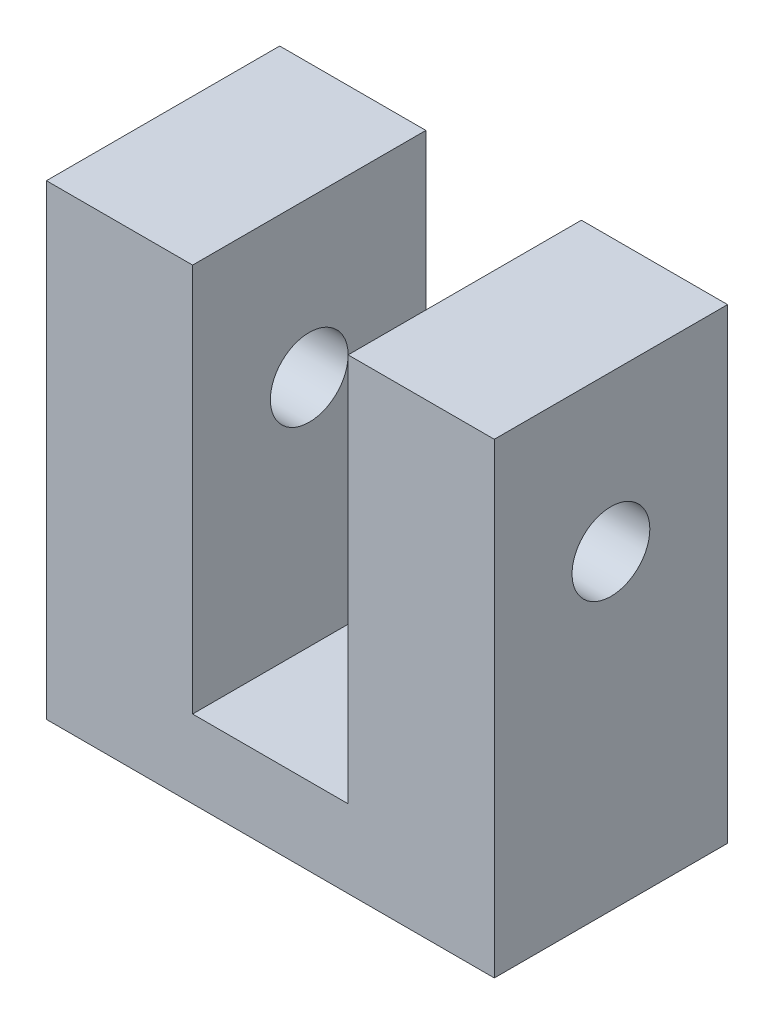
SolidWorks part; units mm, degrees
ref_plane "Front Plane" through (0, 0, 0) normal (0, 0, 1) x (1, 0, 0)
ref_plane "Top Plane" through (0, 0, 0) normal (0, 1, 0) x (1, 0, 0)
ref_plane "Right Plane" through (0, 0, 0) normal (1, 0, 0) x (0, 0, -1)
sketch "Sketch1" plane through (0, 0, 0) normal (0, 0, 1) x (1, 0, 0)
  line L0 (-18.288, 0) -> (-18.288, 38.1)
  line L1 (-18.288, 38.1) -> (-6.35, 38.1)
  line L2 (-6.35, 38.1) -> (-6.35, 6.35)
  line L3 (0, -55) -> (0, 55) construction
  line L4 (6.35, 38.1) -> (6.35, 6.35)
  line L5 (18.288, 38.1) -> (6.35, 38.1)
  line L6 (18.288, 0) -> (18.288, 38.1)
  line L7 (-6.35, 6.35) -> (6.35, 6.35)
  line L8 (-18.288, 0) -> (18.288, 0)
  dimension "D1" = 12.7
  dimension "D2" = 36.576
  dimension "D3" = 38.1
  dimension "D4" = 31.75
extrude "Boss-Extrude1" add sketch "Sketch1" along normal mid plane 19.05
hole_wizard "Hole1" positions "Sketch2" profile "Sketch3" legacy end condition through all
sketch "Sketch2" plane through (18.288, 0, 0) normal (1, 0, 0) x (0, 0, -1)
  point P0 (0, 25.4)
  point P4 (0, 0)
  dimension "D1" = 25.4
sketch "Sketch3" plane through (18.288, 25.4, 0) normal (0, 1, 0) x (0, 0, -1)
  line L0 (0, 0) -> (0, 36.576)
  line L1 (0, 36.576) -> (3.175, 36.576)
  line L2 (3.175, 36.576) -> (3.175, 0)
  line L3 (3.175, 0) -> (0, 0)
  line L4 (0, 110) -> (0, -10) construction
  dimension "Diameter" = 6.35
  dimension "Depth" = 36.576
hole_wizard "Hole2" positions "Sketch4" profile "Sketch5" legacy
sketch "Sketch4" plane through (0, 0, 0) normal (0, -1, 0) x (-1, 0, 0)
  line L2 (-18.288, -9.525) -> (-18.288, 9.525) construction
  line L3 (18.288, -9.525) -> (-18.288, -9.525) construction
  point P0 (-13.208, -3.175)
  point P2 (12.192, -3.175)
  point P13 (0, 0)
  dimension "D1" = 25.4
  dimension "D2" = 5.08
  dimension "D3" = 6.35
sketch "Sketch5" plane through (13.208, 0, 3.175) normal (1, 0, 0) x (0, 0, -1)
  line L0 (0, 0) -> (0, 12.7)
  line L1 (0, 12.7) -> (3.175, 12.7)
  line L2 (3.175, 12.7) -> (3.175, 0)
  line L3 (3.175, 0) -> (0, 0)
  line L4 (0, 110) -> (0, -10) construction
  dimension "Diameter" = 6.35
  dimension "Depth" = 12.7
